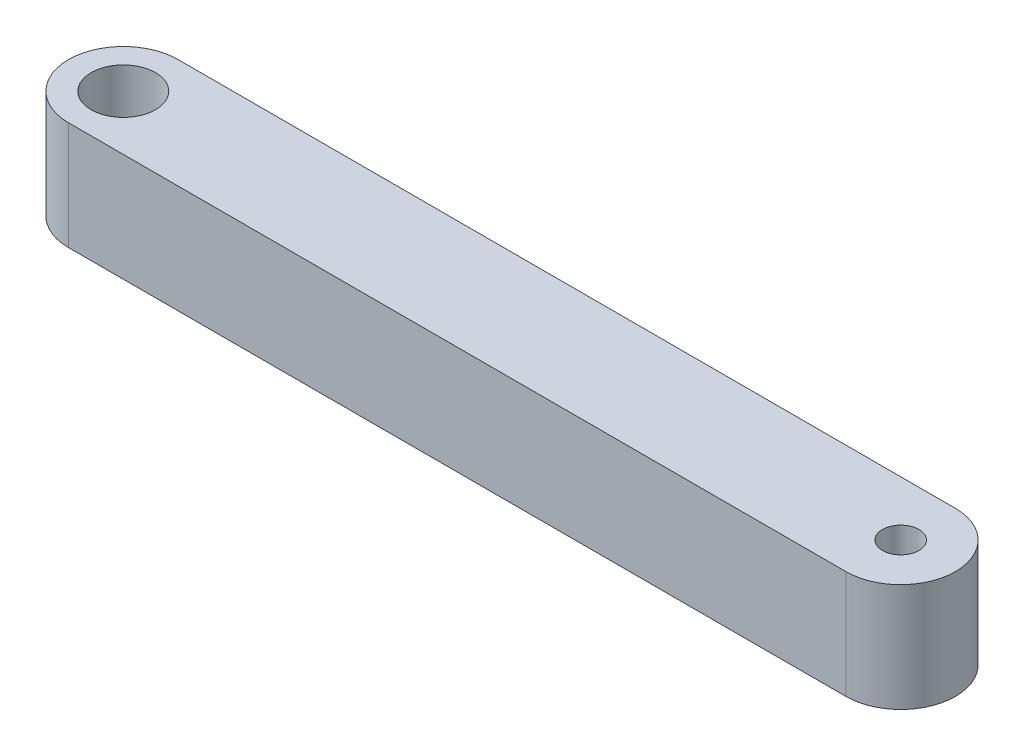
SolidWorks part; units mm, degrees
ref_plane "Front Plane" through (0, 0, 0) normal (0, 0, 1) x (1, 0, 0)
ref_plane "Top Plane" through (0, 0, 0) normal (0, 1, 0) x (1, 0, 0)
ref_plane "Right Plane" through (0, 0, 0) normal (1, 0, 0) x (0, 0, -1)
sketch "Sketch1" plane through (0, 0, 0) normal (0, 1, 0) x (1, 0, 0)
  line L1 (-17.2988, 4.646) -> (21.0552, 4.646)
  line L3 (-17.2988, -0.7579) -> (21.0552, -0.7579)
  arc A0 (-17.2988, 4.646) -> (-17.2988, -0.7579) centre (-17.2988, 1.9441) ccw
  arc A1 (21.0552, -0.7579) -> (21.0552, 4.646) centre (21.0552, 1.9441) ccw
  circle A2 centre (-17.2988, 1.9441) radius 1.5875
  circle A3 centre (21.0552, 1.9441) radius 0.9
  dimension "D1" = 38.354
extrude "Boss-Extrude1" add sketch "Sketch1" along normal blind 5.334
